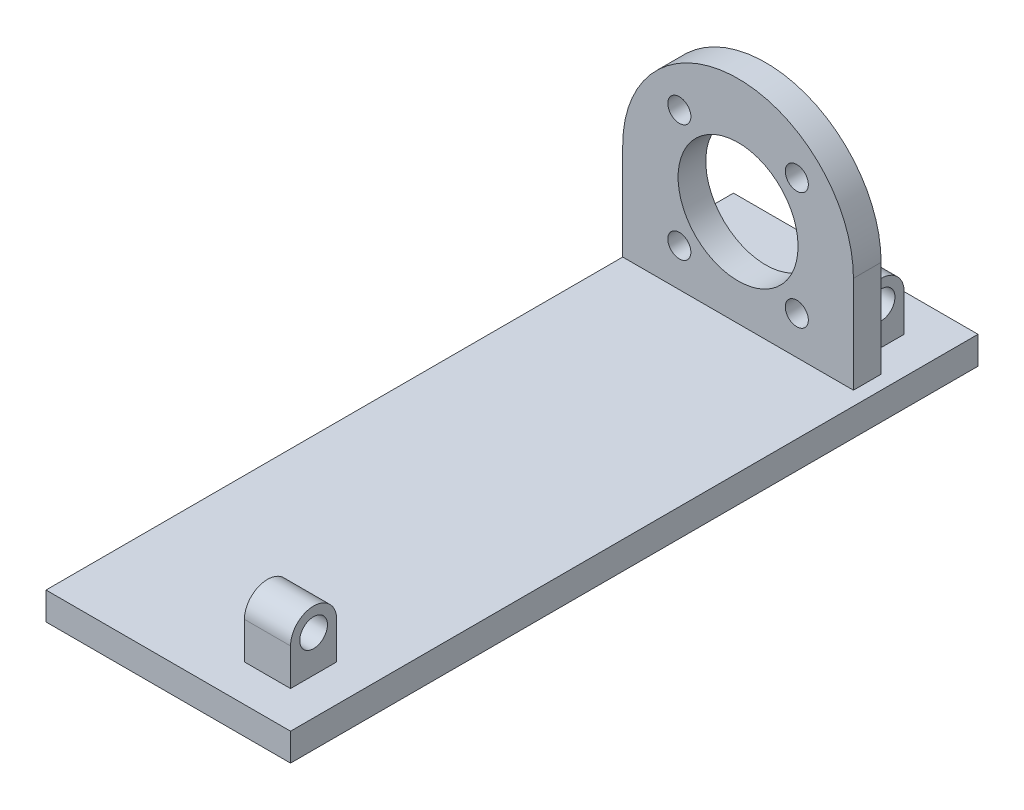
SolidWorks part; units mm, degrees
ref_plane "Alzado" through (0, 0, 0) normal (0, 0, 1) x (1, 0, 0)
ref_plane "Planta" through (0, 0, 0) normal (0, 1, 0) x (1, 0, 0)
ref_plane "Vista lateral" through (0, 0, 0) normal (1, 0, 0) x (0, 0, -1)
sketch "Croquis1" plane through (0, 0, 0) normal (0, 0, 1) x (1, 0, 0)
  line L1 (25, -9) -> (-25, -9)
  line L2 (25, -9) -> (25, 9)
  line L4 (-25, -9) -> (-25, 9)
  line L5 (25, -9) -> (-25, 9) construction
  line L6 (25, 9) -> (-25, -9) construction
  arc A0 (25, 9) -> (-25, 9) centre (0, 9) ccw
  circle A1 centre (0, 9) radius 13
  point P0 (0, 0)
  dimension "D3" = 26
  dimension "D1" = 50
  dimension "D2" = 18
extrude "Saliente-Extruir1" add sketch "Croquis1" along normal mid plane 6
sketch "Croquis2" plane through (0, -9, 0) normal (0, -1, 0) x (1, 0, 0)
  line L4 (-25, -3) -> (25, -3)
  line L5 (25, -3) -> (25, 3)
  line L6 (25, 3) -> (-25, 3)
  line L7 (-25, 3) -> (-25, -3)
  line L8 (-25, -3) -> (25, -3)
  line L9 (25, -3) -> (25, 3)
  line L10 (25, 3) -> (-25, 3)
  line L11 (-25, 3) -> (-25, -3)
  dimension "D1" = 0
extrude "Saliente-Extruir2" add sketch "Croquis2" along normal blind 9
sketch "Croquis3" plane through (0, 0, 3) normal (0, 0, 1) x (1, 0, 0)
  line L0 (-25, 9) -> (-25, -18) construction
  line L5 (25, -18) -> (-25, -18)
  line L6 (25, -18) -> (25, -12)
  line L7 (25, -12) -> (-25, -12)
  line L8 (-25, -18) -> (-25, -12)
  dimension "D1" = 6
extrude "Saliente-Extruir3" add sketch "Croquis3" along normal blind 107 separate body
sketch "Croquis4" plane through (0, 0, 3) normal (0, 0, -1) x (-1, 0, 0)
  line L4 (-25, -12) -> (-25, -18)
  line L5 (-25, -12) -> (-25, -18)
  line L6 (25, -18) -> (25, -12)
  line L7 (-25, -18) -> (25, -18)
  line L10 (25, -18) -> (25, -12)
  line L12 (-25, -18) -> (25, -18)
  line L13 (25, -12) -> (-25, -12)
  line L14 (25, -12) -> (-25, -12)
  dimension "D1" = 0
extrude "Saliente-Extruir4" add sketch "Croquis4" along normal up to surface (6 mm away)
sketch "Croquis5" plane through (0, 0, 3) normal (0, 0, 1) x (1, 0, 0)
  line L0 (0, 9) -> (0, 14.4513) construction
  line L1 (0, 9) -> (12.7279, 21.7279) construction
  circle A0 centre (0, 9) radius 18 construction
  circle A1 centre (12.7279, 21.7279) radius 2.5
  circle A2 centre (12.7279, -3.7279) radius 2.5
  circle A3 centre (-12.7279, -3.7279) radius 2.5
  circle A4 centre (-12.7279, 21.7279) radius 2.5
  dimension "D1" = 36
  dimension "D3" = 5
  dimension "D2" = 45
  dimension "D4" = 4
extrude "Cortar-Extruir1" cut sketch "Croquis5" against normal through all
sketch "Croquis6" plane through (0, 0, 110) normal (0, 0, 1) x (1, 0, 0)
  line L4 (25, -18) -> (25, -12)
  line L5 (25, -12) -> (-25, -12)
  line L6 (-25, -12) -> (-25, -18)
  line L7 (-25, -18) -> (25, -18)
  line L8 (25, -18) -> (25, -12)
  line L9 (25, -12) -> (-25, -12)
  line L10 (-25, -12) -> (-25, -18)
  line L11 (-25, -18) -> (25, -18)
  dimension "D1" = 0
extrude "Saliente-Extruir5" add sketch "Croquis6" along normal blind 18
sketch "Croquis7" plane through (0, 0, -3) normal (0, 0, -1) x (-1, 0, 0)
  line L0 (-25, -18) -> (-25, 9) construction
  line L1 (25, -18) -> (-25, -18)
  line L2 (25, -18) -> (25, -12)
  line L3 (25, -12) -> (-25, -12)
  line L4 (-25, -18) -> (-25, -12)
  dimension "D1" = 6
extrude "Saliente-Extruir6" add sketch "Croquis7" along normal blind 18
ref_plane "Plano1" through (0, 0, 53.5) normal (0, 0, -1) x (-1, 0, 0)
ref_plane "Plano2" through (20, 0, 0) normal (1, 0, 0) x (0, 0, -1)
sketch "Croquis8" plane through (20, 0, 0) normal (1, 0, 0) x (0, 0, -1)
  line L0 (21, -12) -> (3, -12) construction
  line L2 (3, -4) -> (3, -12)
  line L3 (3, -12) -> (13, -12)
  line L4 (13, -4) -> (13, -12)
  line L5 (3, -12) -> (3, 9) construction
  arc A0 (13, -4) -> (3, -4) centre (8, -4) ccw
  circle A1 centre (8, -4) radius 3
  dimension "D3" = 6
  dimension "D1" = 8
  dimension "D2" = 10
extrude "Saliente-Extruir7" add sketch "Croquis8" against normal blind 10
mirror "Simetría1" about plane through (0, 0, 53.5) normal (0, 0, -1) of "Saliente-Extruir7"
sketch "Croquis9" plane through (25, 0, 0) normal (1, 0, 0) x (0, 0, -1)
  line L8 (-128, -18) -> (21, -18)
  line L9 (21, -18) -> (21, -12)
  line L10 (21, -12) -> (3, -12)
  line L11 (3, -12) -> (3, 9)
  line L12 (3, 9) -> (-3, 9)
  line L13 (-3, 9) -> (-3, -12)
  line L14 (-3, -12) -> (-128, -12)
  line L15 (-128, -12) -> (-128, -18)
  line L16 (-128, -18) -> (21, -18)
  line L17 (21, -18) -> (21, -12)
  line L18 (21, -12) -> (3, -12)
  line L22 (3, -12) -> (-128, -12)
  line L23 (-128, -12) -> (-128, -18)
  point P2 (2.1, -12)
  dimension "D1" = 0
extrude "Saliente-Extruir8" add sketch "Croquis9" along normal blind 3
